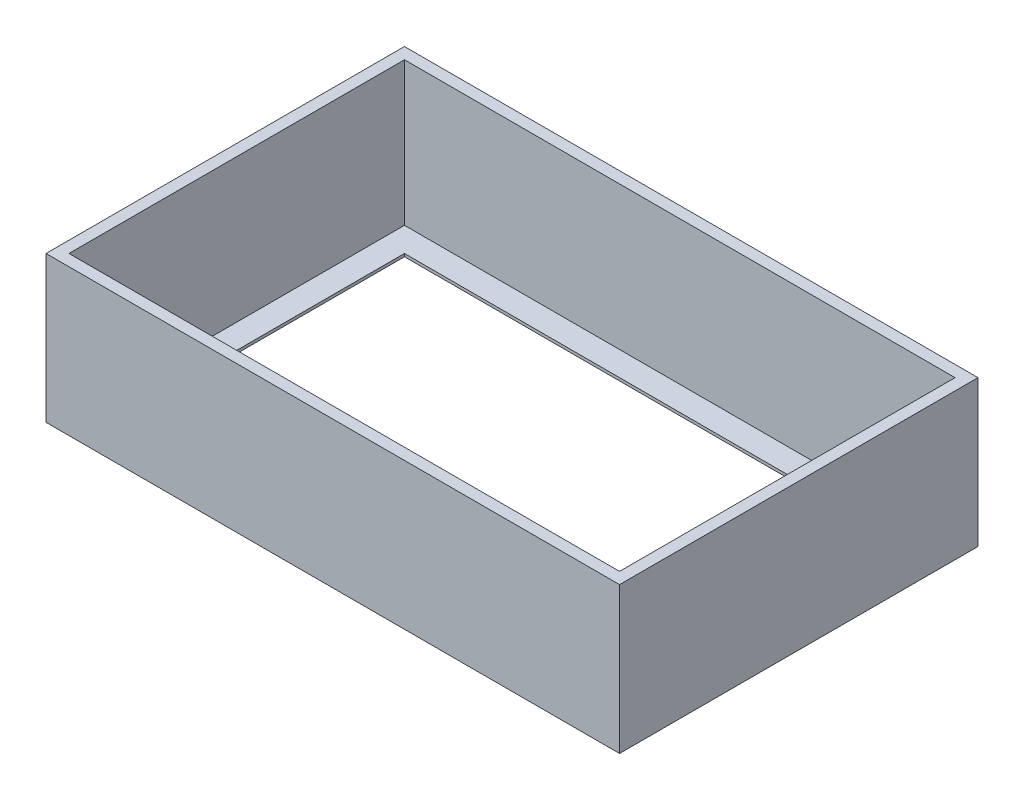
SolidWorks part; units mm, degrees
ref_plane "Front Plane" through (0, 0, 0) normal (0, 0, 1) x (1, 0, 0)
ref_plane "Top Plane" through (0, 0, 0) normal (0, 1, 0) x (1, 0, 0)
ref_plane "Right Plane" through (0, 0, 0) normal (1, 0, 0) x (0, 0, -1)
sketch "Sketch1" plane through (0, 0, 0) normal (0, 1, 0) x (1, 0, 0)
  line L1 (0.9738, -0.7755) -> (80.9738, -0.7755)
  line L2 (0.9738, -0.7755) -> (0.9738, -50.7755)
  line L3 (0.9738, -50.7755) -> (80.9738, -50.7755)
  line L4 (80.9738, -0.7755) -> (80.9738, -50.7755)
  dimension "D1" = 50
  dimension "D2" = 80
extrude "Boss-Extrude1" add sketch "Sketch1" along normal blind 0.4
sketch "Sketch2" plane through (0, 0.4, 0) normal (0, 1, 0) x (1, 0, 0)
  line L0 (2.5738, -2.3755) -> (2.5738, -49.1755)
  line L1 (0.9738, -0.7755) -> (80.9738, -0.7755)
  line L2 (0.9738, -0.7755) -> (0.9738, -50.7755)
  line L3 (0.9738, -50.7755) -> (80.9738, -50.7755)
  line L4 (80.9738, -0.7755) -> (80.9738, -50.7755)
  line L5 (2.5738, -49.1755) -> (79.3738, -49.1755)
  line L6 (79.3738, -2.3755) -> (79.3738, -49.1755)
  line L7 (2.5738, -2.3755) -> (79.3738, -2.3755)
  dimension "D1" = 1.6
extrude "Boss-Extrude2" add sketch "Sketch2" along normal blind 20
sketch "Sketch3" plane through (0, 0, 0) normal (0, -1, 0) x (-1, 0, 0)
  line L0 (-5.9738, -5.7755) -> (-5.9738, -45.7755)
  line L1 (-80.9738, -0.7755) -> (-0.9738, -0.7755) construction
  line L2 (-0.9738, -0.7755) -> (-0.9738, -50.7755) construction
  line L3 (-0.9738, -50.7755) -> (-80.9738, -50.7755) construction
  line L4 (-80.9738, -50.7755) -> (-80.9738, -0.7755) construction
  line L5 (-5.9738, -45.7755) -> (-75.9738, -45.7755)
  line L6 (-75.9738, -5.7755) -> (-75.9738, -45.7755)
  line L7 (-5.9738, -5.7755) -> (-75.9738, -5.7755)
  dimension "D1" = 5
  dimension "D2" = 5
  dimension "D3" = 5
  dimension "D4" = 5
extrude "Cut-Extrude1" cut sketch "Sketch3" against normal through all
